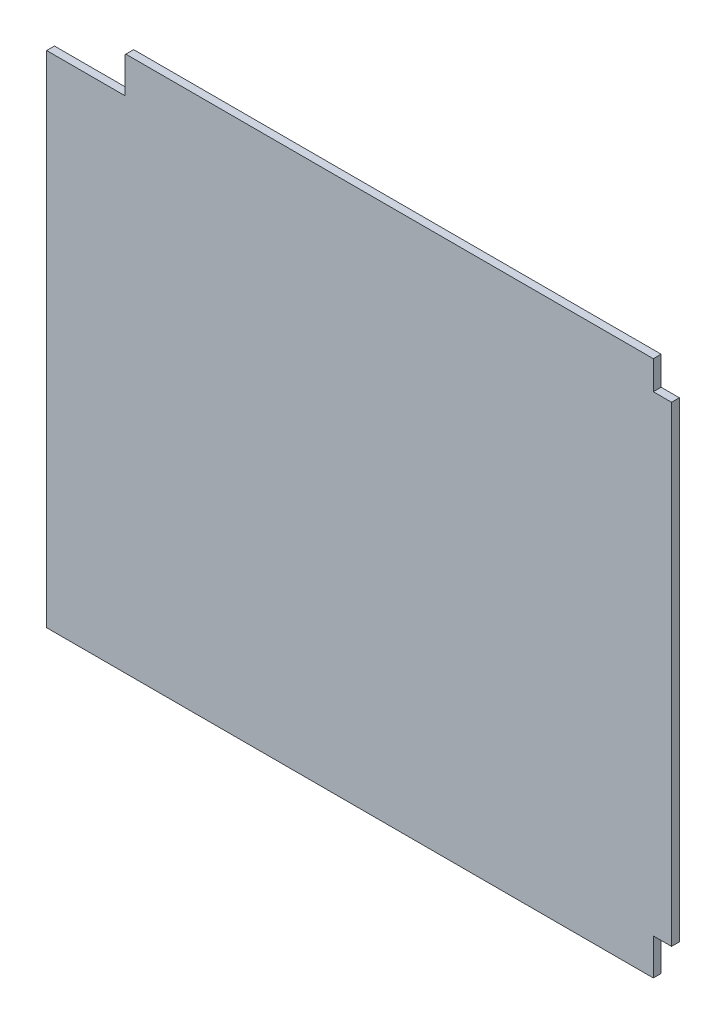
SolidWorks part; units mm, degrees
ref_plane "Front Plane" through (0, 0, 0) normal (0, 0, 1) x (1, 0, 0)
ref_plane "Top Plane" through (0, 0, 0) normal (0, 1, 0) x (1, 0, 0)
ref_plane "Right Plane" through (0, 0, 0) normal (1, 0, 0) x (0, 0, -1)
sketch "Sketch1" plane through (0, 0, 0) normal (0, 0, 1) x (1, 0, 0)
  line L0 (-118.0385, -110.5504) -> (116.9615, -110.5504)
  line L1 (116.9615, -96.5504) -> (123.9615, -96.5504)
  line L2 (123.9615, -96.5504) -> (123.9615, 86.4496)
  line L3 (123.9615, 86.4496) -> (116.9615, 86.4496)
  line L4 (116.9615, 86.4496) -> (116.9615, 97.4496)
  line L5 (116.9615, 97.4496) -> (-74.0385, 97.4496)
  line L6 (-74.0385, 97.4496) -> (-87.0385, 97.4496)
  line L7 (-87.0385, 97.4496) -> (-88.0385, 96.4496)
  line L8 (-88.0385, 96.4496) -> (-88.0385, 83.4496)
  line L9 (116.9615, -110.5504) -> (116.9615, -96.5504)
  line L10 (-88.0385, 83.4496) -> (-118.0385, 83.4496)
  line L11 (-118.0385, 83.4496) -> (-118.0385, -110.5504)
  line L12 (-117.0385, -109.5504) -> (115.9615, -109.5504)
  line L13 (115.9615, -109.5504) -> (115.9615, -95.5504)
  line L14 (115.9615, -95.5504) -> (122.9615, -95.5504)
  line L15 (122.9615, -95.5504) -> (122.9615, 85.4496)
  line L16 (122.9615, 85.4496) -> (115.9615, 85.4496)
  line L17 (115.9615, 85.4496) -> (115.9615, 96.4496)
  line L18 (115.9615, 96.4496) -> (-74.0385, 96.4496)
  line L19 (-74.0385, 96.4496) -> (-86.6242, 96.4496)
  line L20 (-86.6242, 96.4496) -> (-87.0385, 96.0354)
  line L21 (-87.0385, 96.0354) -> (-87.0385, 82.4496)
  line L22 (-87.0385, 82.4496) -> (-117.0385, 82.4496)
  line L23 (-117.0385, 82.4496) -> (-117.0385, -109.5504)
extrude "Boss-Extrude1" add sketch "Sketch1" along normal blind 3 contours L22 L23 L12 L13 L14 L15 L16 L17 L18 L19 L20 L21
